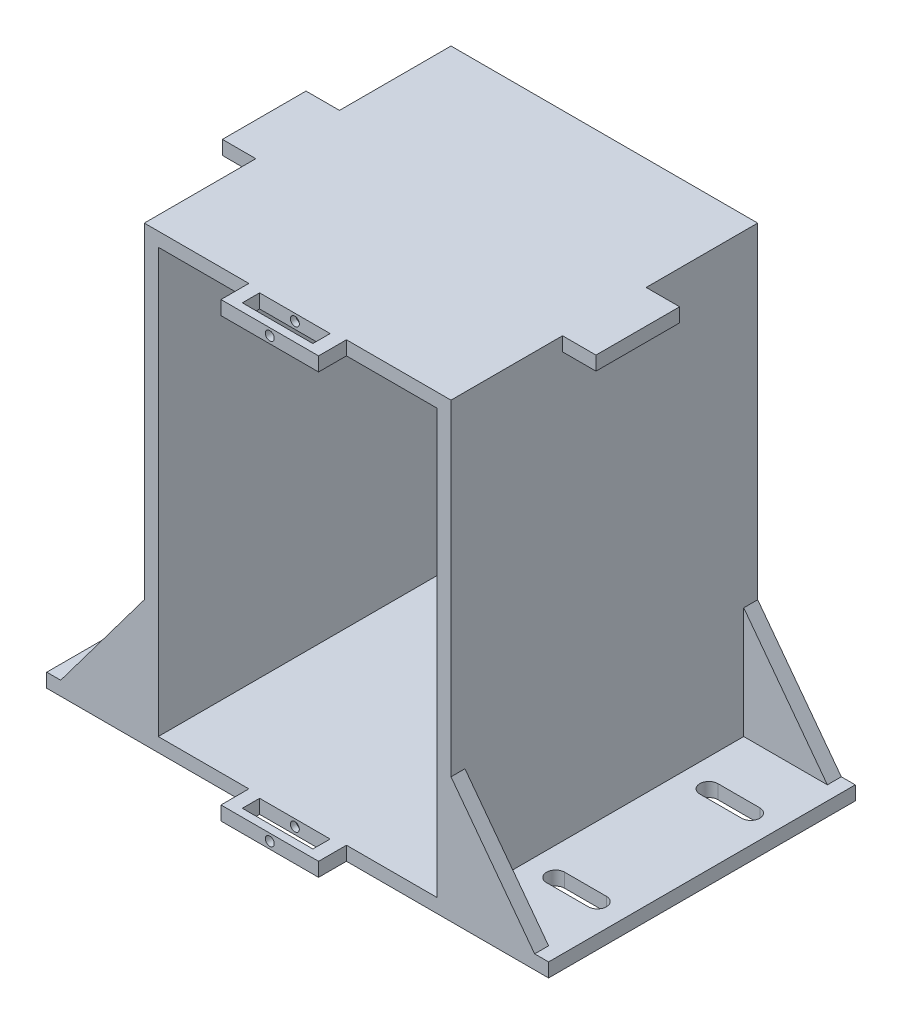
SolidWorks part; units mm, degrees
other "Markup1"
sketch "Sketch10" plane through (-80, -81, -55) normal (-1, 0, 0) x (0, 0, 1)
ref_plane "Front Plane" through (0, 0, 0) normal (0, 0, 1) x (1, 0, 0)
ref_plane "Top Plane" through (0, 0, 0) normal (0, 1, 0) x (1, 0, 0)
ref_plane "Right Plane" through (0, 0, 0) normal (1, 0, 0) x (0, 0, -1)
sketch "Sketch1" plane through (0, 0, 0) normal (0, 0, 1) x (1, 0, 0)
  line L1 (-55, -81) -> (55, -81)
  line L2 (-55, -81) -> (-55, 81)
  line L3 (-55, 81) -> (55, 81)
  line L4 (55, -81) -> (55, 81)
  line L5 (-55, -81) -> (55, 81) construction
  line L6 (-55, 81) -> (55, -81) construction
  point P0 (0, 0)
  dimension "D1" = 110
  dimension "D2" = 162
extrude "Boss-Extrude1" add sketch "Sketch1" along normal mid plane 110
shell "Shell1" thickness 5
sketch "Sketch2" plane through (0, 0, 0) normal (0, 0, 1) x (1, 0, 0)
  line L0 (0, 0) -> (0, -81) construction
  line L1 (-55, -81) -> (-90, -81)
  line L2 (-55, -81) -> (-55, -76)
  line L3 (-55, -76) -> (-90, -76)
  line L4 (-90, -81) -> (-90, -76)
  line L5 (-55, -81) -> (55, -81) construction
  line L6 (55, -76) -> (90, -76)
  line L7 (90, -81) -> (90, -76)
  line L8 (55, -81) -> (90, -81)
  line L9 (55, -81) -> (55, -76)
  dimension "D1" = 180
  dimension "D2" = 5
extrude "Boss-Extrude2" add sketch "Sketch2" along normal mid plane 110
sketch "Sketch3" plane through (0, 0, 0) normal (0, 0, 1) x (1, 0, 0)
  line L0 (-85, -76) -> (-55, -36)
  line L1 (-55, -76) -> (-90, -76) construction
  line L2 (-55, 81) -> (-55, -76) construction
  line L3 (-55, -36) -> (-55, -76)
  line L4 (-55, -76) -> (-85, -76)
  line L5 (0, 0) -> (0, -81) construction
  line L6 (-90, -81) -> (90, -81) construction
  line L7 (55, -36) -> (55, -76)
  line L8 (85, -76) -> (55, -36)
  line L9 (55, -76) -> (85, -76)
  dimension "D1" = 40
  dimension "D2" = 30
extrude "Boss-Extrude3" add sketch "Sketch3" along normal mid plane 110
sketch "Sketch12" plane through (0, 0, 0) normal (0, 0, 1) x (1, 0, 0)
  line L0 (0, 0) -> (0, -32.4908) construction
  line L1 (-90, -76) -> (-55, -76)
  line L2 (-90, -76) -> (-90, -36)
  line L3 (-90, -36) -> (-55, -36)
  line L4 (-55, -76) -> (-55, -36)
  line L5 (90, -36) -> (55, -36)
  line L6 (55, -76) -> (55, -36)
  line L7 (90, -76) -> (55, -76)
  line L8 (90, -76) -> (90, -36)
extrude "Cut-Extrude5" cut sketch "Sketch12" against normal mid plane 100
sketch "Sketch5" plane through (0, -76, 0) normal (0, 1, 0) x (1, 0, 0)
  line L0 (-90, -55) -> (-55, 0) construction
  line L1 (0, 0) -> (11.0866, 0) construction
  line L2 (-55, 50) -> (-55, -50) construction
  line L3 (0, 0) -> (0, 13.6043) construction
  line L4 (-90, 55) -> (-55, 0) construction
  line L5 (90, -55) -> (55, 0) construction
  line L6 (90, 55) -> (55, 0) construction
  line L7 (-80, 27.5) -> (-65, 27.5) construction
  line L8 (-80, 30.75) -> (-65, 30.75)
  line L9 (-80, 24.25) -> (-65, 24.25)
  line L10 (80, 27.5) -> (65, 27.5) construction
  line L11 (80, 30.75) -> (65, 30.75)
  line L12 (80, 24.25) -> (65, 24.25)
  line L13 (80, -27.5) -> (65, -27.5) construction
  line L14 (80, -30.75) -> (65, -30.75)
  line L15 (80, -24.25) -> (65, -24.25)
  line L16 (-80, -27.5) -> (-65, -27.5) construction
  line L17 (-80, -30.75) -> (-65, -30.75)
  line L18 (-80, -24.25) -> (-65, -24.25)
  arc A0 (-80, 30.75) -> (-80, 24.25) centre (-80, 27.5) ccw
  arc A1 (-65, 24.25) -> (-65, 30.75) centre (-65, 27.5) ccw
  arc A2 (80, 30.75) -> (80, 24.25) centre (80, 27.5) cw
  arc A3 (65, 24.25) -> (65, 30.75) centre (65, 27.5) cw
  arc A4 (80, -30.75) -> (80, -24.25) centre (80, -27.5) ccw
  arc A5 (65, -24.25) -> (65, -30.75) centre (65, -27.5) ccw
  arc A6 (-80, -30.75) -> (-80, -24.25) centre (-80, -27.5) cw
  arc A7 (-65, -24.25) -> (-65, -30.75) centre (-65, -27.5) cw
  point P6 (-72.5, 27.5)
  point P17 (72.5, 27.5)
  point P29 (72.5, -27.5)
  point P36 (-72.5, -27.5)
  dimension "D1" = 6.5
  dimension "D2" = 15
extrude "Cut-Extrude1" cut sketch "Sketch5" against normal blind 5
sketch "Sketch6" plane through (0, 0, 0) normal (0, 0, 1) x (1, 0, 0)
  line L0 (0, 0) -> (0, 33.5938) construction
  line L1 (-55, 81) -> (-67, 81)
  line L2 (-55, 81) -> (-55, 76)
  line L3 (-55, 76) -> (-67, 76)
  line L4 (-67, 81) -> (-67, 76)
  line L5 (55, 76) -> (67, 76)
  line L6 (67, 81) -> (67, 76)
  line L7 (55, 81) -> (67, 81)
  line L8 (55, 81) -> (55, 76)
  dimension "D1" = 5
  dimension "D2" = 12
extrude "Boss-Extrude4" add sketch "Sketch6" along normal mid plane 30
sketch "Sketch7" plane through (0, 0, 0) normal (1, 0, 0) x (0, 0, -1)
  line L0 (0, 0) -> (-21.3387, 0) construction
  line L1 (-55, 81) -> (-65, 81)
  line L2 (-55, 81) -> (-55, 76)
  line L3 (-55, 76) -> (-65, 76)
  line L4 (-65, 81) -> (-65, 76)
  line L5 (-55, -76) -> (-65, -76)
  line L6 (-65, -81) -> (-65, -76)
  line L7 (-55, -81) -> (-65, -81)
  line L8 (-55, -81) -> (-55, -76)
  dimension "D1" = 5
  dimension "D2" = 10
extrude "Boss-Extrude5" add sketch "Sketch7" along normal mid plane 35
sketch "Sketch8" plane through (0, 81, 0) normal (0, 1, 0) x (1, 0, 0)
  line L0 (0, 0) -> (0, -65) construction
  line L5 (17.5, -65) -> (-17.5, -65) construction
  line L6 (-12.65, -56) -> (12.65, -56)
  line L7 (-12.65, -56) -> (-12.65, -62.2)
  line L8 (-12.65, -62.2) -> (12.65, -62.2)
  line L9 (12.65, -56) -> (12.65, -62.2)
  line L10 (-12.65, -56) -> (12.65, -62.2) construction
  line L11 (-12.65, -62.2) -> (12.65, -56) construction
  line L12 (-17.5, -55) -> (-55, -55) construction
  point P2 (0, -59.1)
  dimension "D1" = 25.3
  dimension "D2" = 6.2
  dimension "D3" = 1
extrude "Cut-Extrude2" cut sketch "Sketch8" against normal up to surface (162 mm away)
sketch "Sketch9" plane through (0, 0, 65) normal (0, 0, 1) x (1, 0, 0)
  line L0 (-17.5, -76) -> (17.5, -81) construction
  line L1 (0, 0) -> (19.745, 0) construction
  circle A0 centre (0, -78.5) radius 1.6
  circle A1 centre (0, 78.5) radius 1.6
  dimension "D1" = 3.2
extrude "Cut-Extrude3" cut sketch "Sketch9" against normal blind 11
